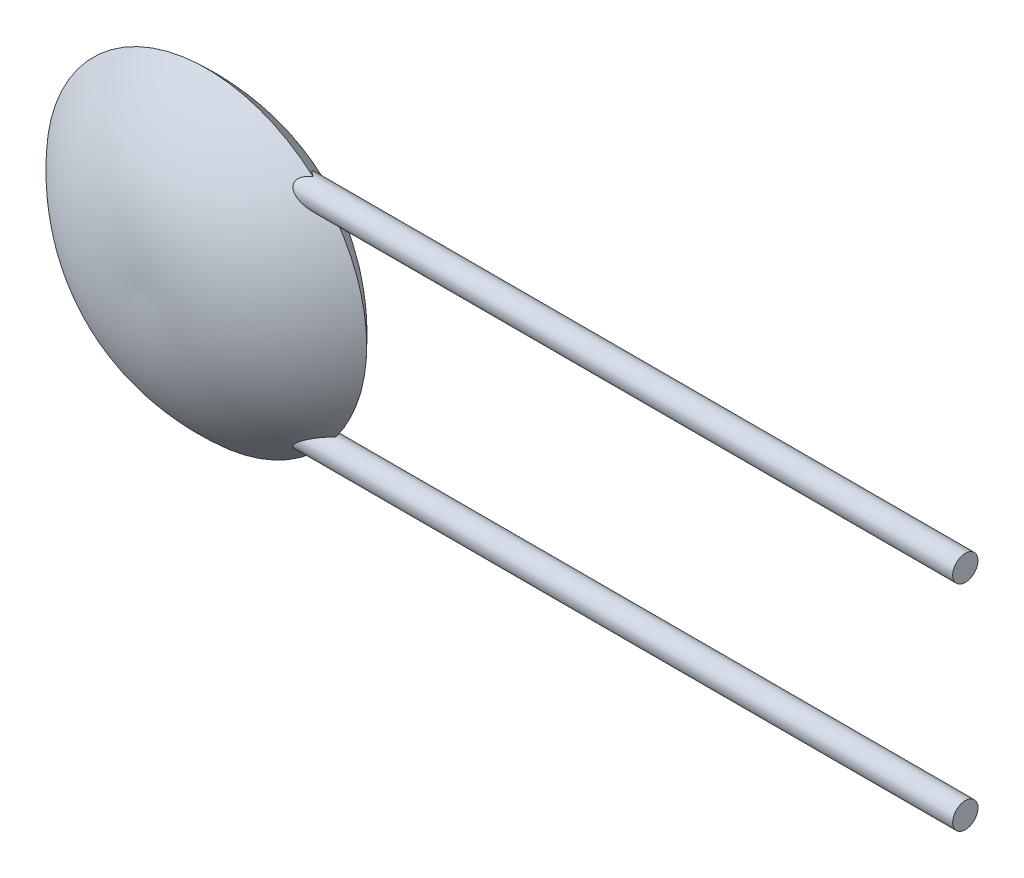
SolidWorks part; units mm, degrees
ref_plane "Front Plane" through (0, 0, 0) normal (0, 0, 1) x (1, 0, 0)
ref_plane "Top Plane" through (0, 0, 0) normal (0, 1, 0) x (1, 0, 0)
ref_plane "Right Plane" through (0, 0, 0) normal (1, 0, 0) x (0, 0, -1)
sketch "Sketch3" plane through (0, 0, 0) normal (0, 1, 0) x (1, 0, 0)
  line L0 (0, 0) -> (1.9, 0)
  line L1 (0, -0.8) -> (0, 0.8)
  line L2 (-55, 0) -> (55, 0) construction
  spline S0 degree 2 poles (0, 0.8) (1.1069, 0.865) (1.9, 0) knots 0 0 0 1 1 1
  spline S1 degree 2 poles (0, -0.8) (1.1069, -0.865) (1.9, 0) knots 0 0 0 1 1 1
  dimension "D1" = 1.9
  dimension "D2" = 0.8
revolve "Revolve1" add sketch "Sketch3" angle 360 about L1
sketch "Sketch4" plane through (0, 0, 0) normal (1, 0, 0) x (0, 0, -1)
  line L0 (0, 1.9) -> (0, -1.9) construction
  circle A0 centre (0, 1.27) radius 0.15
  dimension "D1" = 0.3
  dimension "D2" = 1.27
ref_plane "Plane1" through (0, 1.27, 0) normal (0, 1, 0) x (1, 0, 0)
sketch "Sketch5" plane through (0, 1.27, 0) normal (0, 1, 0) x (1, 0, 0)
  line L0 (0, 0) -> (9, 0)
  point P6 (3.75, 0)
  dimension "D1" = 9
sweep "Sweep1" add profiles "Sketch4" path "Sketch5"
mirror "Mirror1" about plane through (0, 0, 0) normal (0, 1, 0) of "Sweep1"
